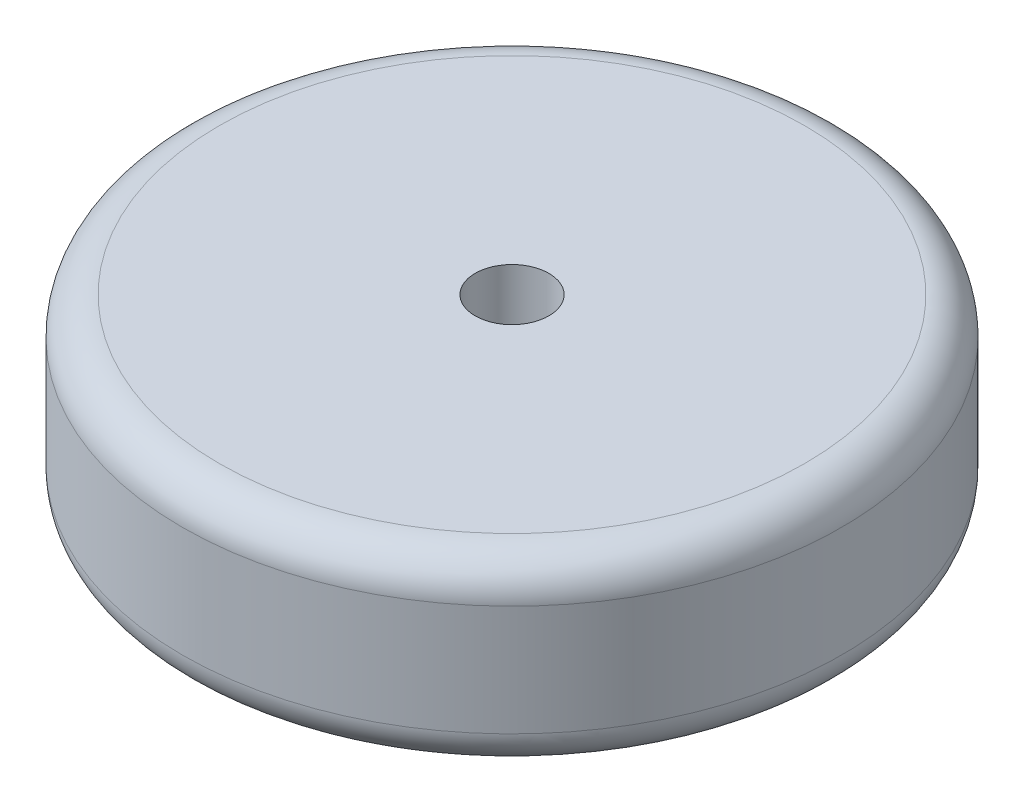
SolidWorks part; units mm, degrees
material "Custom Plastic"
ref_plane "Front Plane" through (0, 0, 0) normal (0, 0, 1) x (1, 0, 0)
ref_plane "Top Plane" through (0, 0, 0) normal (0, 1, 0) x (1, 0, 0)
ref_plane "Right Plane" through (0, 0, 0) normal (1, 0, 0) x (0, 0, -1)
sketch "Sketch1" plane through (0, 0, 0) normal (0, 1, 0) x (1, 0, 0)
  circle A0 centre (0, 0) radius 8.94
  dimension "D1" = 17.88
extrude "Boss-Extrude1" add sketch "Sketch1" along normal blind 5
fillet "Fillet1" radius 1 2 edges at (0, 0, 8.94) (0, 5, 8.94)
sketch "Sketch2" plane through (0, 5, 0) normal (0, 1, 0) x (1, 0, 0)
  circle A0 centre (0, 0) radius 1
  dimension "D1" = 2
extrude "Cut-Extrude1" cut sketch "Sketch2" against normal up to next
